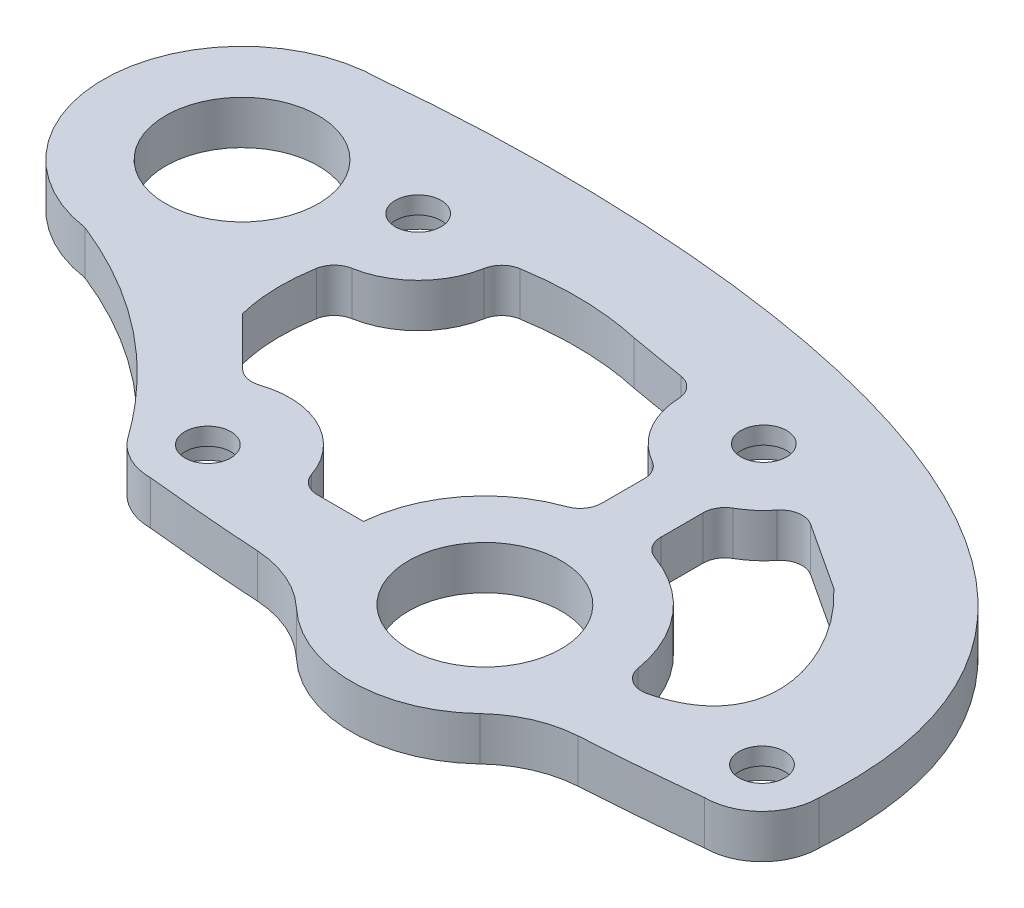
SolidWorks part; units mm, degrees
ref_plane "Front" through (0, 0, 0) normal (0, 0, 1) x (1, 0, 0)
ref_plane "Top" through (0, 0, 0) normal (0, 1, 0) x (1, 0, 0)
ref_plane "Right" through (0, 0, 0) normal (1, 0, 0) x (0, 0, -1)
sketch "Sketch1" plane through (0, 0, 0) normal (0, 1, 0) x (1, 0, 0)
  line L4 (-17.0303, 28.4901) -> (-7.3922, 26.8382)
  line L5 (14.6922, 17.2966) -> (6.8189, 22.4483)
  line L6 (-34.2218, 12.0137) -> (-28.8615, 6.6534)
  line L7 (-17.9737, 1.0488) -> (-12.1794, 1.0488)
  line L9 (-2.7023, 11.922) -> (-2.7023, 18.575)
  line L11 (2.7023, 11.922) -> (2.7023, 18.575)
  circle A3 centre (-46.4745, 24.2108) radius 7
  circle A13 centre (-25.4, 0) radius 2.1
  circle A14 centre (25.4, 0) radius 2.1
  arc A15 (-29.7806, -2.8822) -> (-25.4, -5.2438) centre (-25.4, 0) ccw
  arc A16 (25.4, -5.2438) -> (30.6438, 0) centre (25.4, 0) ccw
  arc A17 (-46.4745, 36.9348) -> (-48.2765, 11.6151) centre (-46.4745, 24.2108) ccw
  circle A18 centre (0, 25.5713) radius 2.1
  circle A22 centre (-34.1163, 28.0012) radius 2.1
  circle A23 centre (0, 0) radius 7
  arc A24 (-10.4361, -6.366) -> (10.4361, -6.366) centre (0, 0) ccw
  arc A25 (-7.3922, 26.8382) -> (-2.7023, 18.575) centre (0, 25.5713) ccw
  arc A26 (-17.9737, 1.0488) -> (-28.8615, 6.6534) centre (-25.4, 0) ccw
  arc A27 (-34.1163, 20.5012) -> (-26.6163, 28.0012) centre (-34.1163, 28.0012) ccw
  arc A29 (-10.4361, -6.366) -> (10.4361, -6.366) centre (0, 0) ccw
  arc A30 (12.2245, 0) -> (2.7023, 11.922) centre (0, 0) ccw
  arc A31 (2.7023, 18.575) -> (6.8189, 22.4483) centre (0, 25.5713) ccw
  arc A32 (-2.7023, 11.922) -> (-12.1794, 1.0488) centre (0, 0) ccw
  spline S0 degree 3 poles (-48.2765, 11.6151) (-40.6637, 8.5838) (-34.415, 3.6353) (-29.5304, -3.2306) knots 0.158174 0.158174 0.158174 0.158174 1 1 1 1
  spline S1 degree 3 poles (-46.4745, 36.9348) (-23.1642, 39.3519) (33.3739, 38.1202) (30.6438, 0) knots 0 0 0 0 1 1 1 1
  spline S2 degree 2 poles (-25.4, -5.2438) (-17.918, -6.0392) (-10.4361, -6.366) knots 0 0 0 0.294566 0.294566 0.294566
  spline S3 degree 2 poles (-34.1163, 20.5012) (-35.2188, 15.9946) (-34.2218, 12.0137) knots 0 0 0 0.526441 0.526441 0.526441
  spline S4 degree 2 poles (10.4361, -6.366) (17.918, -6.0392) (25.4, -5.2438) knots 0.705434 0.705434 0.705434 1 1 1
  spline S5 degree 3 poles (-26.6163, 28.0012) (-22.4157, 28.9074) (-18.3232, 28.9166) (-14.3388, 28.0288) knots 0 0 0 0 0.632388 0.632388 0.632388 0.632388
  spline S6 degree 3 poles (14.6922, 17.2966) (20.9366, 11.5178) (24.0154, 1.1795) (12.2245, 0) knots 0.294732 0.294732 0.294732 0.294732 1 1 1 1
  point P0 (0, 0)
  point P9 (0, 0)
  point P21 (0, 15.2039)
  point P39 (0, 0)
  dimension "D2" = 14
  dimension "D3" = 4.2
  dimension "D4" = 4.2
  dimension "D1" = 14
  dimension "D5" = 50.8
  dimension "D6" = 4.2
  dimension "D7" = 4.2
extrude "Boss-Extrude1" add sketch "Sketch1" along normal blind 4
fillet "Fillet1" radius 10 2 edges at (10.4361, 2, 6.366) (-10.4361, 2, 6.366)
sketch "Sketch2" plane through (0, 0, 0) normal (0, -1, 0) x (1, 0, 0)
  circle A0 centre (0, -25.5713) radius 3.9
  circle A1 centre (25.4, 0) radius 3.9
  circle A2 centre (-25.4, 0) radius 3.9
  circle A3 centre (-34.1163, -28.0012) radius 3.9
extrude "Cut-Extrude1" cut sketch "Sketch2" against normal blind 2.4
fillet "Fillet2" radius 2 11 edges at (-7.3922, 2, -26.8382) (-26.6163, 2, -28.0012) (-28.8615, 2, -6.6534) (-17.9737, 2, -1.0488) (12.2245, 2, 0) (-34.1163, 2, -20.5012) (2.7023, 2, -11.922) (2.7023, 2, -18.575) (6.8189, 2, -22.4483) (-2.7023, 2, -11.922) (-2.7023, 2, -18.575)
